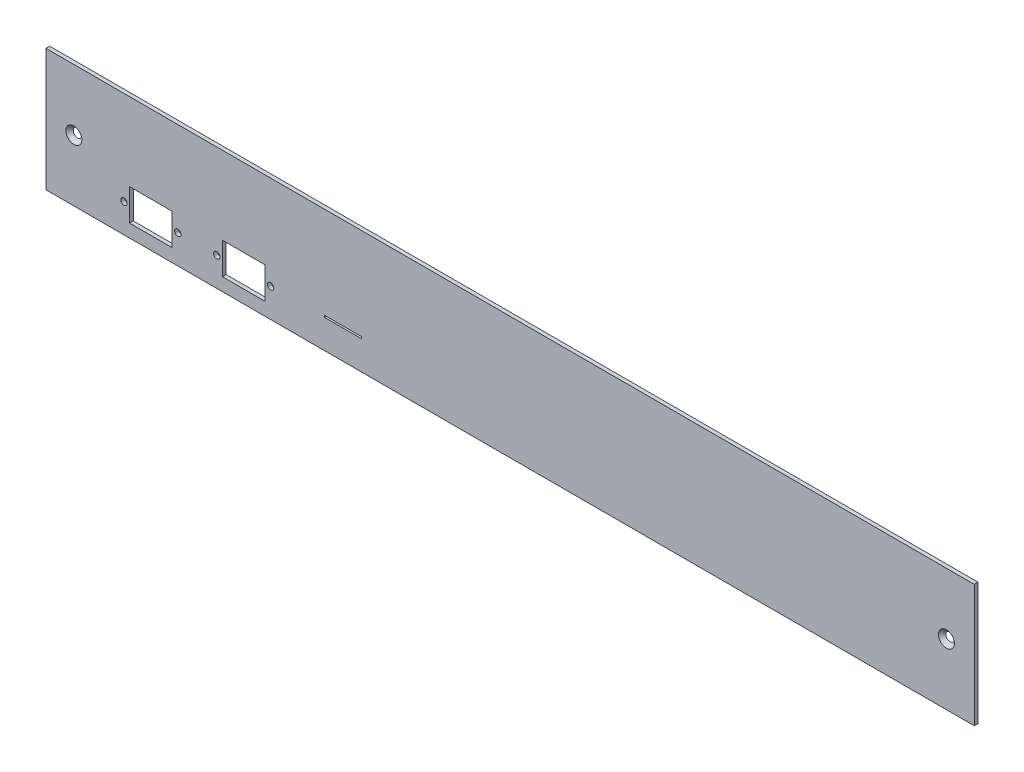
SolidWorks part; units mm, degrees
ref_plane "Ebene vorne" through (0, 0, 0) normal (0, 0, 1) x (1, 0, 0)
ref_plane "Ebene oben" through (0, 0, 0) normal (0, 1, 0) x (1, 0, 0)
ref_plane "Ebene rechts" through (0, 0, 0) normal (1, 0, 0) x (0, 0, -1)
sketch "Skizze1" plane through (0, 0, 0) normal (0, 0, 1) x (1, 0, 0)
  line L0 (-339.9038, 3) -> (160.0962, 3)
  line L1 (160.0962, 3) -> (160.0962, -63)
  line L2 (160.0962, -63) -> (130.0947, -63)
  line L3 (130.0947, -63) -> (130.0947, -71)
  line L5 (130.0947, -71) -> (-309.9023, -71)
  line L6 (-309.9023, -71) -> (-309.9023, -63)
  line L7 (-309.9023, -63) -> (-316.9038, -63)
  line L8 (-316.9038, -63) -> (-339.9038, -63)
  line L9 (-339.9038, -63) -> (-339.9038, 3)
  line L10 (-299.9038, -46) -> (-277.0438, -46)
  line L11 (-299.9038, -46) -> (-299.9038, -63.15)
  line L12 (-299.9038, -63.15) -> (-277.0438, -63.15)
  line L13 (-277.0438, -46) -> (-277.0438, -63.15)
  line L14 (-219.9038, -53.5) -> (-199.9038, -53.5)
  line L15 (-219.9038, -53.5) -> (-219.9038, -54.5)
  line L16 (-219.9038, -54.5) -> (-199.9038, -54.5)
  line L17 (-199.9038, -53.5) -> (-199.9038, -54.5)
  line L22 (-237.0438, -46) -> (-237.0438, -63.15)
  line L23 (-259.9038, -46) -> (-259.9038, -63.15)
  line L24 (-237.0438, -46) -> (-259.9038, -46)
  line L25 (-259.9038, -63.15) -> (-237.0438, -63.15)
  circle A0 centre (-273.9738, -54.575) radius 1.7
  circle A1 centre (-302.9738, -54.575) radius 1.7
  circle A4 centre (-233.9738, -54.575) radius 1.7
  circle A5 centre (-262.9738, -54.575) radius 1.7
  point P41 (-219.9038, -53.5)
  dimension "D7" = 3.4
  dimension "D8" = 3.4
  dimension "D9" = 29
  dimension "D15" = 2
  dimension "D1" = 1
  dimension "D2" = 20
  dimension "D3" = 120
  dimension "D4" = 17.5
  dimension "D5" = 22.86
  dimension "D6" = 17.15
  dimension "D10" = 3.07
  dimension "D11" = 8.575
  dimension "D12" = 25
  dimension "D13" = 40
  dimension "D14" = 8.575
  dimension "D16" = 74
  dimension "D17" = 90
extrude "Aufsatz-Linear austragen1" add sketch "Skizze1" along normal blind 2 contours L0 L1 L2 L3 L5 L6 L7 L8 L9
hole_wizard "Formsenkung für M4 Senkschraube mit Innensechskant1" positions "Skizze2" profile "Skizze3" countersink size "M4" standard "DIN" end condition through all
sketch "Skizze2" plane through (0, 0, 2) normal (0, 0, 1) x (1, 0, 0)
  line L0 (-339.9038, -30) -> (160.0962, -30) construction
  line L1 (-339.9038, -63) -> (-339.9038, 3) construction
  line L2 (160.0962, 3) -> (160.0962, -63) construction
  point P11 (-324.9038, -30)
  point P13 (145.0962, -30)
  dimension "D1" = 15
  dimension "D2" = 15
sketch "Skizze3" plane through (145.0962, -30, 2) normal (1, 0, 0) x (0, -1, 0)
  line L0 (0, 0) -> (0, 2)
  line L1 (0, 2) -> (2.25, 2)
  line L2 (2.25, 2) -> (2.25, 2.05)
  line L3 (2.25, 2.05) -> (4.3, 0)
  line L5 (4.3, 0) -> (0, 0)
  line L6 (-2.25, 2.05) -> (-4.3, 0) construction
  line L11 (0, -6.35) -> (0, 107.95) construction
  dimension "Bohrerdurchmesser" = 4.5
  dimension "Bohrungstiefe" = 2
  dimension "Senkdurchmesser (Oben)" = 8.6
  dimension "Senkwinkel (Oben)" = 90
sketch "Skizze4" plane through (0, 0, 2) normal (0, 0, 1) x (1, 0, 0)
  line L0 (-294.9038, -39) -> (-271.9038, -39)
  line L1 (-294.9038, -39) -> (-294.9038, -56)
  line L2 (-294.9038, -56) -> (-271.9038, -56)
  line L3 (-271.9038, -39) -> (-271.9038, -56)
  line L4 (-189.9038, -46.5) -> (-169.9038, -46.5)
  line L5 (-189.9038, -46.5) -> (-189.9038, -47.5)
  line L6 (-189.9038, -47.5) -> (-169.9038, -47.5)
  line L7 (-169.9038, -46.5) -> (-169.9038, -47.5)
  line L12 (130.0947, -71) -> (-309.9023, -71) construction
  line L13 (-339.9038, -63) -> (-339.9038, 3) construction
  line L14 (-244.9038, -39) -> (-221.9038, -39)
  line L15 (-244.9038, -39) -> (-244.9038, -56)
  line L16 (-244.9038, -56) -> (-221.9038, -56)
  line L17 (-221.9038, -39) -> (-221.9038, -56)
  circle A0 centre (-268.9038, -47.5) radius 1.7
  circle A1 centre (-297.9038, -47.5) radius 1.7
  circle A4 centre (-218.9038, -47.5) radius 1.7
  circle A5 centre (-247.9038, -47.5) radius 1.7
  dimension "D5" = 3.4
  dimension "D6" = 3.4
  dimension "D16" = 8.5
  dimension "D7" = 42
  dimension "D9" = 8.5
  dimension "D13" = 3
  dimension "D15" = 29
  dimension "D14" = 8.5
  dimension "D17" = 23.5
  dimension "D1" = 1
  dimension "D2" = 20
  dimension "D3" = 68
  dimension "D4" = 17
  dimension "D8" = 71
  dimension "D10" = 8.5
  dimension "D11" = 32
  dimension "D12" = 2
  dimension "D21" = 45
  dimension "D22" = 24.5
  dimension "D23" = 150
extrude "Schnitt-Linear austragen1" cut sketch "Skizze4" against normal blind 10
sketch "Skizze5" plane through (0, 0, 0) normal (0, 0, -1) x (-1, 0, 0)
  line L0 (-160.0962, 3) -> (-160.0962, -63) construction
  line L5 (309.9038, -26) -> (144.9038, -26)
  line L6 (309.9038, -26) -> (309.9038, -34)
  line L7 (309.9038, -34) -> (144.9038, -34)
  line L8 (144.9038, -26) -> (144.9038, -34)
  line L14 (-130.0962, -26) -> (-130.0962, -34)
  line L16 (134.9038, -26) -> (134.9038, -34)
  line L21 (339.9038, 3) -> (-160.0962, 3) construction
  line L23 (339.9038, -63) -> (339.9038, 3) construction
  line L24 (-130.0962, -26) -> (-2.5962, -26)
  line L25 (-2.5962, -26) -> (-2.5962, -34)
  line L26 (-2.5962, -34) -> (-130.0962, -34)
  line L27 (134.9038, -26) -> (7.4038, -26)
  line L28 (7.4038, -26) -> (7.4038, -34)
  line L29 (7.4038, -34) -> (134.9038, -34)
  line L36 (339.9038, 3) -> (-160.0962, 3) construction
  point P36 (7.4038, -30)
  dimension "D2" = 29
  dimension "D4" = 8
  dimension "D5" = 10
  dimension "D7" = 30
  dimension "D11" = 29
  dimension "D13" = 195
  dimension "D15" = 30
  dimension "D17" = 8
  dimension "D19" = 8
  dimension "D20" = 10
  dimension "D22" = 127.5
extrude "Mittelschlitz" [suppressed] cut sketch "Skizze5" against normal blind 10
fillet "Verrundung1" [suppressed] radius 4
sketch "Skizze7" plane through (0, 0, 0) normal (0, 0, -1) x (-1, 0, 0)
  line L0 (-130.0947, -71) -> (309.9023, -71) construction
  line L1 (-160.0962, -63) -> (339.9038, -63)
  line L2 (-160.0962, -63) -> (-160.0962, -71)
  line L3 (-160.0962, -71) -> (339.9038, -71)
  line L4 (339.9038, -63) -> (339.9038, -71)
  dimension "D1" = 0
  dimension "D2" = 500
extrude "Schnitt-Linear austragen3" cut sketch "Skizze7" against normal blind 10
